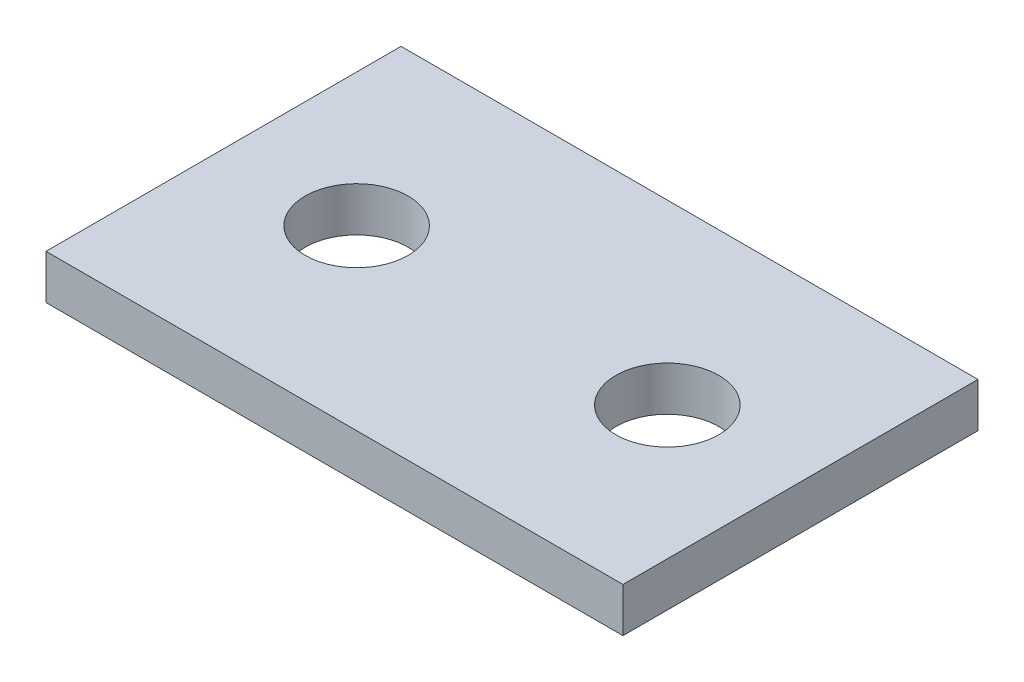
SolidWorks part; units mm, degrees
material "Low Carbon Steel"
ref_plane "Front Plane" through (0, 0, 0) normal (0, 0, 1) x (1, 0, 0)
ref_plane "Top Plane" through (0, 0, 0) normal (0, 1, 0) x (1, 0, 0)
ref_plane "Right Plane" through (0, 0, 0) normal (1, 0, 0) x (0, 0, -1)
sketch "Sketch2" plane through (0, 0, 0) normal (0, 1, 0) x (1, 0, 0)
  line L1 (-41.275, -25.4) -> (41.275, -25.4)
  line L2 (-41.275, -25.4) -> (-41.275, 25.4)
  line L3 (-41.275, 25.4) -> (41.275, 25.4)
  line L4 (41.275, -25.4) -> (41.275, 25.4)
  line L5 (-41.275, -25.4) -> (41.275, 25.4) construction
  line L6 (-41.275, 25.4) -> (41.275, -25.4) construction
  point P0 (0, 0)
  dimension "D1" = 82.55
  dimension "D2" = 50.8
extrude "Boss-Extrude1" add sketch "Sketch2" along normal mid plane 6.35
hole_wizard "1/2 (0.58) Diameter Hole1" positions "Sketch3" profile "Sketch4" hole size "1/2" standard "Peddi Ansi Inch" end condition through all
sketch "Sketch3" plane through (0, 3.175, 0) normal (0, 1, 0) x (1, 0, 0)
  line L0 (-22.225, 0) -> (22.225, 0) construction
  point P0 (-22.225, 0)
  point P2 (22.225, 0)
  dimension "D1" = 44.45
sketch "Sketch4" plane through (-22.225, 3.175, 0) normal (1, 0, 0) x (0, 0, 1)
  line L0 (0, 0) -> (0, 6.35)
  line L1 (0, 6.35) -> (7.366, 6.35)
  line L2 (7.366, 6.35) -> (7.366, 0)
  line L5 (7.366, 0) -> (0, 0)
  line L11 (0, -6.35) -> (0, 107.95) construction
  dimension "Thru Hole Dia." = 14.732
  dimension "Thru Hole Depth" = 6.35
other "Freeze***"
